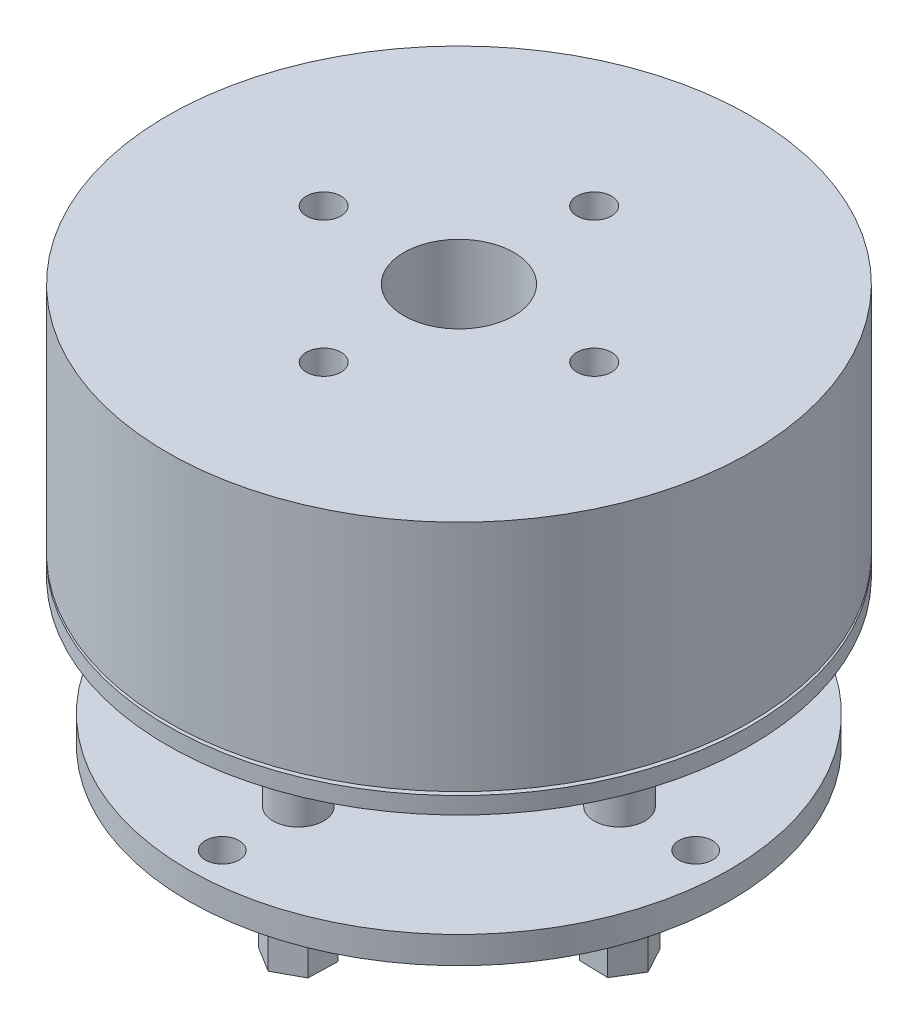
SolidWorks part; units mm, degrees
ref_plane "前视基准面" through (0, 0, 0) normal (0, 0, 1) x (1, 0, 0)
ref_plane "上视基准面" through (0, 0, 0) normal (0, 1, 0) x (1, 0, 0)
ref_plane "右视基准面" through (0, 0, 0) normal (1, 0, 0) x (0, 0, -1)
sketch "草图1" plane through (0, 0, 0) normal (0, 0, 1) x (1, 0, 0)
  line L0 (0, 0) -> (0, 15) construction
  line L1 (0, 15) -> (17.25, 15)
  line L2 (17.25, 15) -> (17.25, 0)
  line L3 (17.25, 0) -> (0, 0)
  line L4 (0, 0) -> (0, 15)
  dimension "D1" = 15
  dimension "D2" = 34.5
revolve "旋转2" add sketch "草图1" angle 360 about L0
sketch "草图2" plane through (0, 0, 0) normal (0, 0, 1) x (1, 0, 0)
  line L0 (0, 0) -> (0, 15.9061) construction
  line L1 (-17.25, 15) -> (-17.25, 0) construction
  line L2 (-17.25, 0) -> (17.25, 0) construction
  line L3 (-17.25, 1.2) -> (-3.5, 1.2)
  line L4 (-17.25, 1.2) -> (-17.25, 1)
  line L5 (-17.25, 1) -> (-3.5, 1)
  line L6 (-3.5, 1.2) -> (-3.5, 1)
  dimension "D1" = 7
  dimension "D2" = 1
  dimension "D3" = 1.2
revolve "切除-旋转2" cut sketch "草图2" angle 360 about L0
sketch "草图3" plane through (0, 15, 0) normal (0, 1, 0) x (1, 0, 0)
  circle A0 centre (0, 0) radius 3.25
  dimension "D1" = 6.5
extrude "切除-拉伸1" cut sketch "草图3" against normal up to next
hole_wizard "M2.5 螺纹孔1" positions "草图5" profile "草图6" tap size "M2.5" standard "GB"
sketch "草图5" plane through (0, 15, 0) normal (0, 1, 0) x (1, 0, 0)
  circle A0 centre (0, 0) radius 8 construction
  point P0 (0, 8)
  dimension "D1" = 16
cosmetic thread "孔螺蚊线1" parameters "D1"=3, "D2"=2.5
sketch "草图6" plane through (0, 15, -8) normal (1, 0, 0) x (0, 0, 1)
  line L0 (0, 0) -> (0, 3.6159)
  line L1 (0, 3.6159) -> (1.025, 3)
  line L2 (1.025, 3) -> (1.025, 0)
  line L5 (1.025, 0) -> (0, 0)
  line L10 (0, 3.6159) -> (-1.025, 3) construction
  line L11 (0, -6.35) -> (0, 107.95) construction
  dimension "螺纹孔钻头直径" = 2.05
  dimension "螺纹孔钻头深度" = 3
  dimension "导头角度" = 118
pattern_circular "阵列(圆周)1" count 4 over 360 about axis through (0, 0, 0) along (0, 1, 0) of "M2.5 螺纹孔1"
sketch "草图8" plane through (0, 0, 0) normal (0, -1, 0) x (1, 0, 0)
  circle A0 centre (0, 0) radius 9.5 construction
  circle A1 centre (0, 9.5) radius 1.5
  circle A2 centre (9.5, 0) radius 1.5
  circle A3 centre (0, -9.5) radius 1.5
  circle A4 centre (-9.5, 0) radius 1.5
  point P14 (0, 0)
  dimension "D1" = 19
  dimension "D2" = 3
  dimension "D3" = 4
extrude "凸台-拉伸1" add sketch "草图8" along normal blind 7
ref_plane "基准面1" through (0, -7, 0) normal (0, -1, 0) x (-1, 0, 0)
sketch "草图9" plane through (0, -7, 0) normal (0, -1, 0) x (-1, 0, 0)
  circle A0 centre (0, 0) radius 16
  point P16 (0, 0)
extrude "凸台-拉伸2" add sketch "草图9" along normal blind 1.6 separate body
sketch "草图11" plane through (0, -8.6, 0) normal (0, -1, 0) x (1, 0, 0)
  line L0 (8.6768, -1.5239) -> (10.4081, -1.4749)
  line L1 (1.5239, 8.6768) -> (1.4749, 10.4081)
  line L2 (1.4749, 10.4081) -> (-0.049, 11.2314)
  line L3 (-0.049, 11.2314) -> (-1.5239, 10.3232)
  line L4 (-1.5239, 10.3232) -> (-1.4749, 8.5919)
  line L5 (-1.4749, 8.5919) -> (0.049, 7.7686)
  line L6 (0.049, 7.7686) -> (1.5239, 8.6768)
  line L7 (10.4081, -1.4749) -> (11.2314, 0.049)
  line L8 (11.2314, 0.049) -> (10.3232, 1.5239)
  line L9 (10.3232, 1.5239) -> (8.5919, 1.4749)
  line L10 (8.5919, 1.4749) -> (7.7686, -0.049)
  line L11 (7.7686, -0.049) -> (8.6768, -1.5239)
  line L12 (-1.5239, -8.6768) -> (-1.4749, -10.4081)
  line L13 (-1.4749, -10.4081) -> (0.049, -11.2314)
  line L14 (0.049, -11.2314) -> (1.5239, -10.3232)
  line L15 (1.5239, -10.3232) -> (1.4749, -8.5919)
  line L16 (1.4749, -8.5919) -> (-0.049, -7.7686)
  line L17 (-0.049, -7.7686) -> (-1.5239, -8.6768)
  line L18 (-8.6768, 1.5239) -> (-10.4081, 1.4749)
  line L19 (-10.4081, 1.4749) -> (-11.2314, -0.049)
  line L20 (-11.2314, -0.049) -> (-10.3232, -1.5239)
  line L21 (-10.3232, -1.5239) -> (-8.5919, -1.4749)
  line L22 (-8.5919, -1.4749) -> (-7.7686, 0.049)
  line L23 (-7.7686, 0.049) -> (-8.6768, 1.5239)
  circle A0 centre (0, 0) radius 9.5 construction
  circle A2 centre (0, 9.5) radius 1.5 construction
  point P32 (0, 0)
  dimension "D1" = 19
  dimension "D2" = 4
extrude "凸台-拉伸3" add sketch "草图11" along normal blind 6
sketch "草图12" plane through (0, -8.6, 0) normal (0, -1, 0) x (1, 0, 0)
  circle A0 centre (0, 0) radius 14 construction
  circle A1 centre (0, 14) radius 1
  circle A2 centre (14, 0) radius 1
  circle A3 centre (0, -14) radius 1
  circle A4 centre (-14, 0) radius 1
  point P14 (0, 0)
  dimension "D1" = 4
extrude "切除-拉伸2" cut sketch "草图12" against normal up to surface (1.6 mm away) and the other way through all up to face at (0, -7, -16)
sketch "草图14" plane through (0, 0, 0) normal (0, 0, 1) x (1, 0, 0)
  line L0 (-17.25, 0) -> (17.25, 0) construction
  line L2 (6, 0) -> (3.25, 0)
  line L3 (6, 0) -> (6, -4.5)
  line L4 (6, -4.5) -> (3.25, -4.5)
  line L5 (3.25, 0) -> (3.25, -4.5)
  line L6 (0, 0) -> (0, -7.4574) construction
  dimension "D1" = 3.25
  dimension "D2" = 6
  dimension "D3" = 4.5
revolve "旋转3" add sketch "草图14" angle 360 about L6
